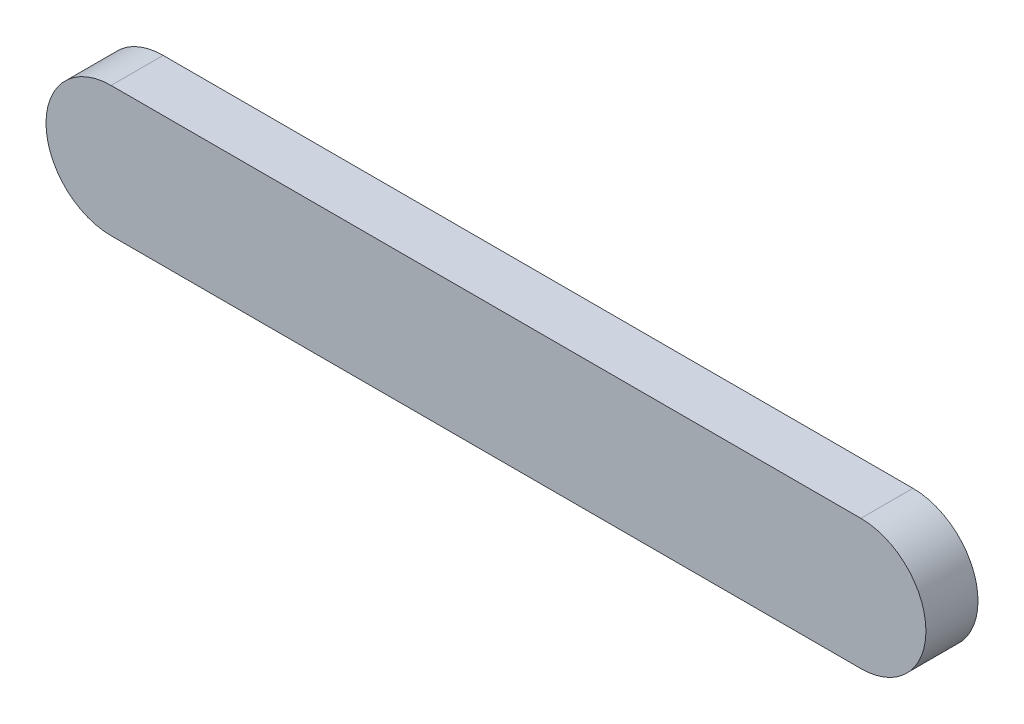
SolidWorks part; units mm, degrees
ref_plane "前视基准面" through (0, 0, 0) normal (0, 0, 1) x (1, 0, 0)
ref_plane "上视基准面" through (0, 0, 0) normal (0, 1, 0) x (1, 0, 0)
ref_plane "右视基准面" through (0, 0, 0) normal (1, 0, 0) x (0, 0, -1)
sketch "草图1" plane through (0, 0, 0) normal (0, 0, 1) x (1, 0, 0)
  line L0 (0, 0) -> (288, 0) construction
  line L1 (0, 25) -> (288, 25)
  line L2 (0, -25) -> (288, -25)
  arc A0 (0, 25) -> (0, -25) centre (0, 0) ccw
  arc A1 (288, -25) -> (288, 25) centre (288, 0) ccw
  point P3 (144, 0)
  dimension "D2" = 25
  dimension "D1" = 288
extrude "凸台-拉伸1" add sketch "草图1" along normal blind 20
